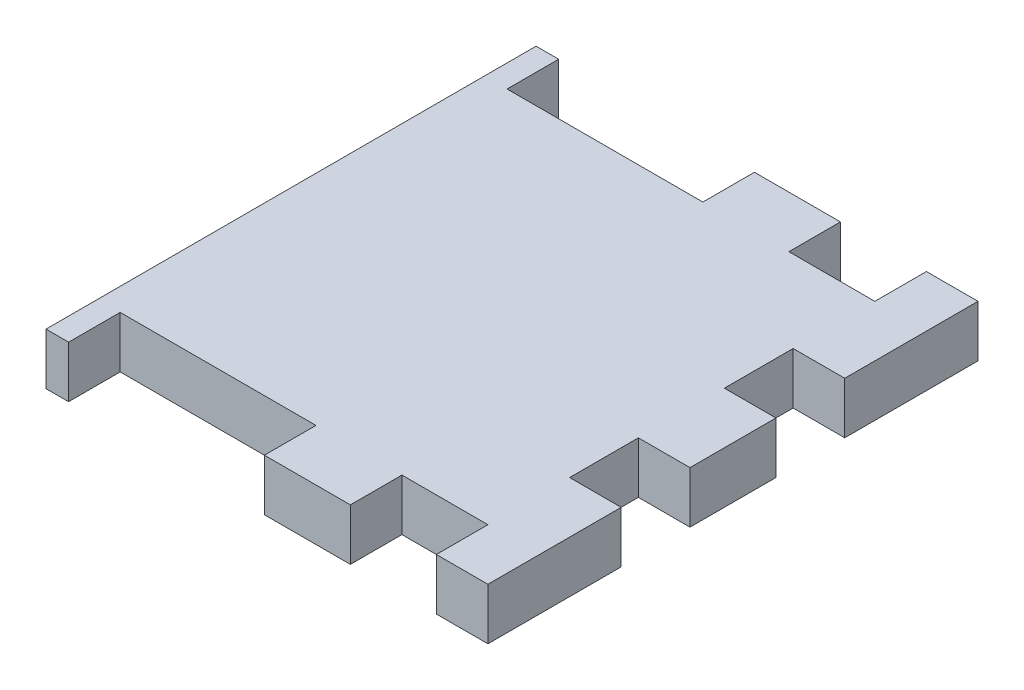
SolidWorks part; units mm, degrees
ref_plane "Front Plane" through (0, 0, 0) normal (0, 0, 1) x (1, 0, 0)
ref_plane "Top Plane" through (0, 0, 0) normal (0, 1, 0) x (1, 0, 0)
ref_plane "Right Plane" through (0, 0, 0) normal (1, 0, 0) x (0, 0, -1)
sketch "Sketch1" plane through (0, 0, 0) normal (0, 1, 0) x (1, 0, 0)
  line L1 (-12.85, 14.25) -> (12.85, 14.25)
  line L2 (-12.85, 14.25) -> (-12.85, -14.25)
  line L3 (-12.85, -14.25) -> (12.85, -14.25)
  line L4 (12.85, 14.25) -> (12.85, -14.25)
  line L5 (-12.85, 14.25) -> (12.85, -14.25) construction
  line L6 (-12.85, -14.25) -> (12.85, 14.25) construction
  point P0 (0, 0)
  dimension "D1" = 28.5
  dimension "D2" = 25.7
extrude "Boss-Extrude1" add sketch "Sketch1" along normal blind 3
sketch "Sketch2" plane through (0, 0, 0) normal (0, -1, 0) x (1, 0, 0)
  line L1 (-4.85, -16.0999) -> (-9.85, -16.0999)
  line L2 (-4.85, -16.0999) -> (-4.85, -11.25)
  line L3 (-4.85, -11.25) -> (-9.85, -11.25)
  line L4 (-9.85, -16.0999) -> (-9.85, -11.25)
  line L5 (-12.85, -14.25) -> (-12.85, 14.25) construction
  line L6 (12.85, 0) -> (-12.85, 0) construction
  line L7 (12.85, 14.25) -> (12.85, -14.25) construction
  line L8 (-4.85, 11.25) -> (-9.85, 11.25)
  line L9 (-9.85, 16.0999) -> (-9.85, 11.25)
  line L10 (-4.85, 16.0999) -> (-9.85, 16.0999)
  line L11 (-4.85, 16.0999) -> (-4.85, 11.25)
  line L12 (-12.85, 14.25) -> (12.85, 14.25) construction
  dimension "D1" = 3
  dimension "D2" = 5
  dimension "D3" = 3
sketch "Sketch3" plane through (0, 0, 0) normal (0, -1, 0) x (1, 0, 0)
  line L0 (12.85, 0) -> (-12.85, 0) construction
  line L1 (12.85, 14.25) -> (12.85, -14.25) construction
  line L2 (-12.85, -14.25) -> (-12.85, 14.25) construction
  line L3 (12.85, -14.25) -> (-12.85, -14.25) construction
  line L4 (9.85, -14.25) -> (4.85, -14.25)
  line L5 (9.85, -14.25) -> (9.85, -11.25)
  line L6 (9.85, -11.25) -> (4.85, -11.25)
  line L7 (4.85, -14.25) -> (4.85, -11.25)
  line L8 (-0.15, -14.25) -> (-0.15, -11.25)
  line L9 (-0.15, -14.25) -> (-5.15, -14.25)
  line L10 (-5.15, -14.25) -> (-5.15, -11.25)
  line L11 (-0.15, -11.25) -> (-5.15, -11.25)
  line L12 (-0.15, 14.25) -> (-5.15, 14.25)
  line L13 (-5.15, 14.25) -> (-5.15, 11.25)
  line L14 (-0.15, 11.25) -> (-5.15, 11.25)
  line L15 (-0.15, 14.25) -> (-0.15, 11.25)
  line L16 (9.85, 11.25) -> (4.85, 11.25)
  line L17 (4.85, 14.25) -> (4.85, 11.25)
  line L18 (9.85, 14.25) -> (4.85, 14.25)
  line L19 (9.85, 14.25) -> (9.85, 11.25)
  line L20 (-9.5362, 11.25) -> (-11.5362, 11.25)
  line L21 (-9.5362, -14.25) -> (-11.5362, -14.25)
  line L22 (-9.5362, -14.25) -> (-9.5362, -11.25)
  line L23 (-9.5362, -11.25) -> (-11.5362, -11.25)
  line L24 (-11.5362, -14.25) -> (-11.5362, -11.25)
  line L25 (-11.5362, 14.25) -> (-11.5362, 11.25)
  line L26 (-9.5362, 14.25) -> (-11.5362, 14.25)
  line L27 (-9.5362, 14.25) -> (-9.5362, 11.25)
  line L28 (12.85, -2.5) -> (9.85, -2.5)
  line L29 (12.85, 6.5) -> (9.85, 6.5)
  line L30 (12.85, 6.5) -> (12.85, 2.5)
  line L31 (12.85, 2.5) -> (9.85, 2.5)
  line L32 (9.85, 6.5) -> (9.85, 2.5)
  line L33 (9.85, -6.5) -> (9.85, -2.5)
  line L34 (12.85, -6.5) -> (9.85, -6.5)
  line L35 (12.85, -6.5) -> (12.85, -2.5)
  dimension "D1" = 3
  dimension "D2" = 5
  dimension "D3" = 3
  dimension "D5" = 3
  dimension "D6" = 2
  dimension "D7" = 3
  dimension "D8" = 4
  dimension "D9" = 5
  dimension "D4" = 2
extrude "Cut-Extrude2" cut sketch "Sketch3" against normal blind 10
extrude "Cut-Extrude3" cut sketch "Sketch2" against normal blind 3
